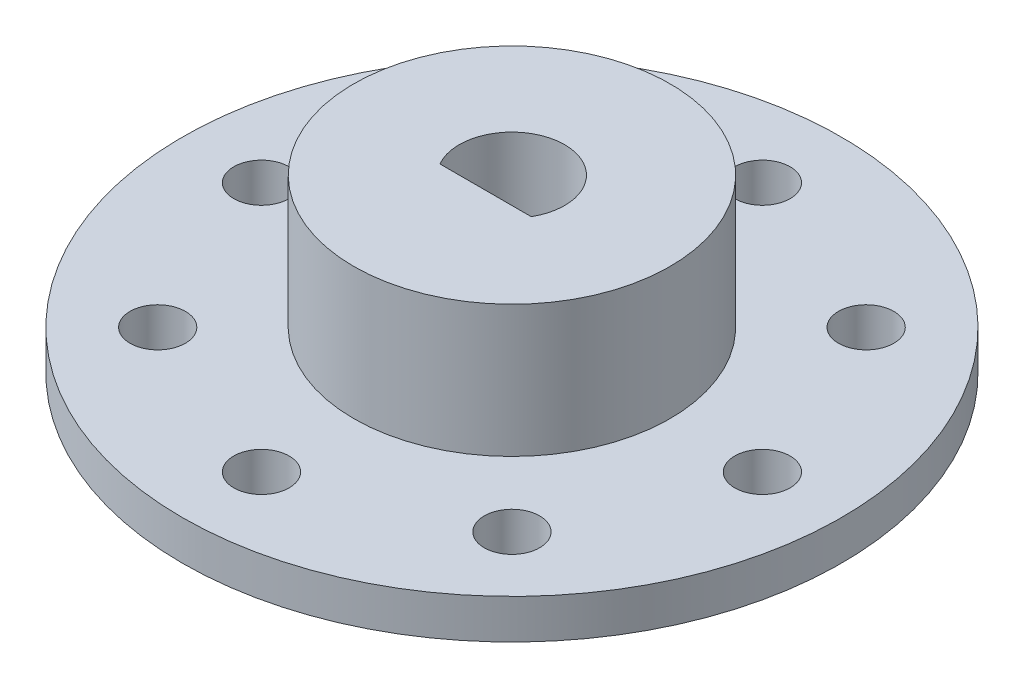
SolidWorks part; units mm, degrees
ref_plane "前视基准面" through (0, 0, 0) normal (0, 0, 1) x (1, 0, 0)
ref_plane "上视基准面" through (0, 0, 0) normal (0, 1, 0) x (1, 0, 0)
ref_plane "右视基准面" through (0, 0, 0) normal (1, 0, 0) x (0, 0, -1)
sketch "草图1" plane through (0, 0, 0) normal (0, 1, 0) x (1, 0, 0)
  circle A0 centre (0, 0) radius 25
  circle A1 centre (0, 19) radius 2.1
  circle A2 centre (13.435, 13.435) radius 2.1
  circle A3 centre (19, 0) radius 2.1
  circle A4 centre (13.435, -13.435) radius 2.1
  circle A5 centre (0, -19) radius 2.1
  circle A6 centre (-13.435, -13.435) radius 2.1
  circle A7 centre (-19, 0) radius 2.1
  circle A8 centre (-13.435, 13.435) radius 2.1
  point P22 (0, 0)
  dimension "D1" = 50
  dimension "D2" = 4.2
  dimension "D3" = 19
  dimension "D4" = 8
extrude "凸台-拉伸1" add sketch "草图1" along normal blind 3
sketch "草图2" plane through (0, 3, 0) normal (0, 1, 0) x (1, 0, 0)
  line L1 (-3.4641, -2) -> (3.4641, -2)
  circle A0 centre (0, 0) radius 12
  arc A1 (3.4641, -2) -> (-3.4641, -2) centre (0, 0) ccw
  dimension "D1" = 24
  dimension "D2" = 8
  dimension "D3" = 2
extrude "凸台-拉伸2" add sketch "草图2" along normal blind 10
sketch "草图3" plane through (0, 13, 0) normal (0, 1, 0) x (1, 0, 0)
  line L0 (-3.4641, -2) -> (3.4641, -2)
  arc A0 (3.4641, -2) -> (-3.4641, -2) centre (0, 0) ccw
extrude "切除-拉伸1" cut sketch "草图3" against normal blind 20
